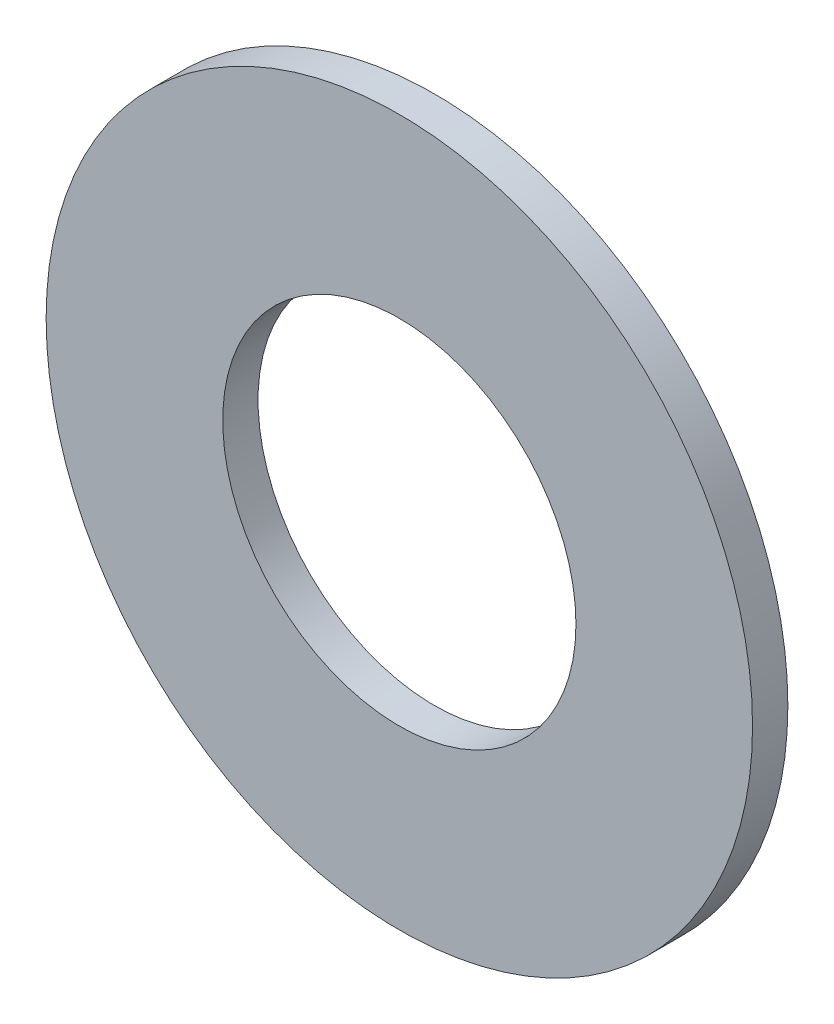
SolidWorks part; units mm, degrees
ref_plane "前视基准面" through (0, 0, 0) normal (0, 0, 1) x (1, 0, 0)
ref_plane "上视基准面" through (0, 0, 0) normal (0, 1, 0) x (1, 0, 0)
ref_plane "右视基准面" through (0, 0, 0) normal (1, 0, 0) x (0, 0, -1)
sketch "草图1" plane through (0, 0, 0) normal (0, 0, 1) x (1, 0, 0)
  circle A0 centre (0, 0) radius 1
  circle A1 centre (0, 0) radius 2
  dimension "D1" = 4
  dimension "D2" = 2
extrude "凸台-拉伸1" add sketch "草图1" along normal mid plane 0.2
